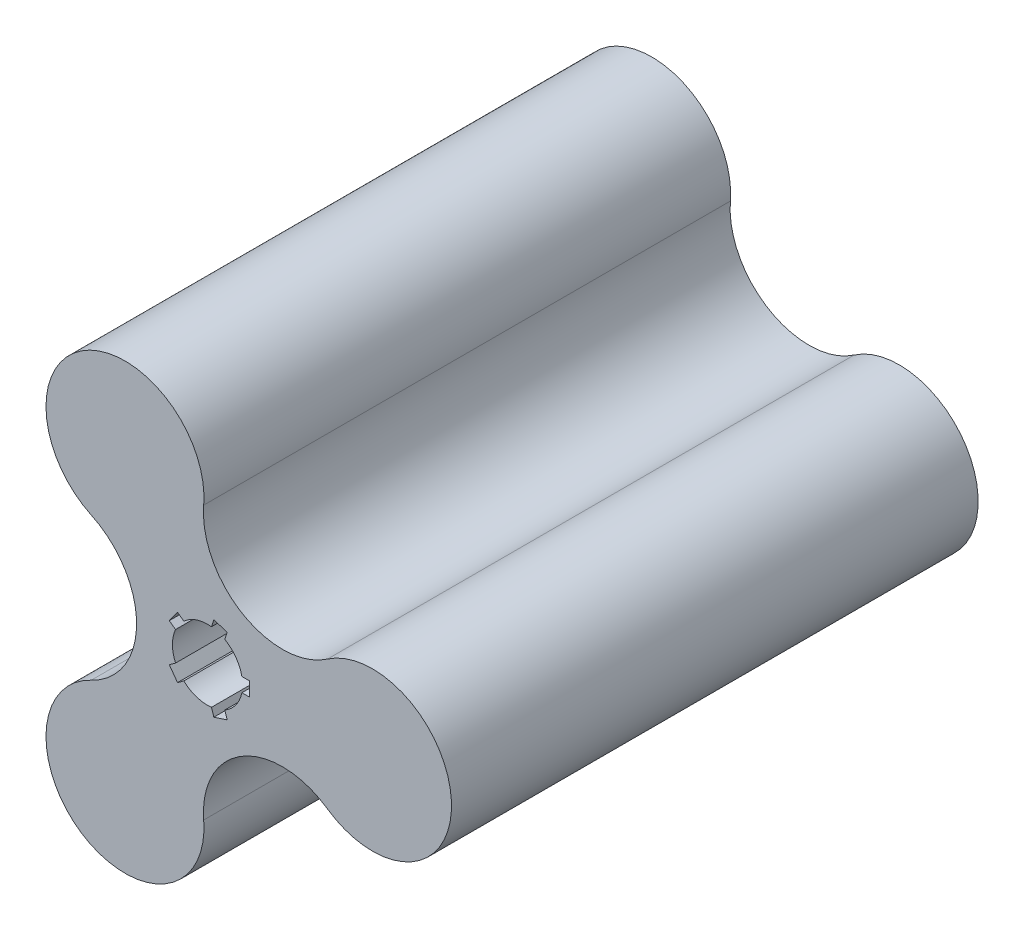
SolidWorks part; units mm, degrees
material "1023 Carbon Steel Sheet (SS)"
ref_plane "Front Plane" through (0, 0, 0) normal (0, 0, 1) x (1, 0, 0)
ref_plane "Top Plane" through (0, 0, 0) normal (0, 1, 0) x (1, 0, 0)
ref_plane "Right Plane" through (0, 0, 0) normal (1, 0, 0) x (0, 0, -1)
sketch "Sketch1" plane through (0, 0, 0) normal (0, 0, 1) x (1, 0, 0)
  arc A0 (34.1725, -18.4852) -> (34.1725, 18.4852) centre (47, 0) ccw
  arc A1 (-33.0949, -20.3516) -> (-1.0775, -38.8368) centre (-23.5, -40.7032) ccw
  arc A2 (-1.0775, 38.8368) -> (-33.0949, 20.3516) centre (-23.5, 40.7032) ccw
  arc A3 (-33.0949, -20.3516) -> (-33.0949, 20.3516) centre (-42.6898, 0) ccw
  arc A4 (-1.0775, 38.8368) -> (34.1725, 18.4852) centre (21.3449, 36.9705) ccw
  arc A5 (34.1725, -18.4852) -> (-1.0775, -38.8368) centre (21.3449, -36.9705) ccw
  point P14 (0, 0)
  point P17 (0, 0)
  dimension "D1" = 45
  dimension "D4" = 45
  dimension "D2" = 47
  dimension "D6" = 40.7032
  dimension "D7" = 47
  dimension "D3" = 3
  dimension "D5" = 3
extrude "Boss-Extrude1" add sketch "Sketch1" against normal blind 150
sketch "Sketch2" plane through (0, 0, 0) normal (0, 0, 1) x (1, 0, 0)
  line L5 (9.798, 2) -> (12, 2)
  line L7 (9.798, -2) -> (12, -2)
  line L8 (12, 2) -> (12, -2)
  line L11 (4.9298, -8.7004) -> (5.6103, -10.7946)
  line L12 (5.6103, -10.7946) -> (1.8061, -12.0307)
  line L13 (1.1256, -9.9364) -> (1.8061, -12.0307)
  line L15 (-6.7511, -7.3771) -> (-8.5326, -8.6715)
  line L16 (-8.5326, -8.6715) -> (-10.8838, -5.4354)
  line L17 (-9.1023, -4.1411) -> (-10.8838, -5.4354)
  line L19 (-9.1023, 4.1411) -> (-10.8838, 5.4354)
  line L20 (-10.8838, 5.4354) -> (-8.5326, 8.6715)
  line L21 (-6.7511, 7.3771) -> (-8.5326, 8.6715)
  line L23 (1.1256, 9.9364) -> (1.8061, 12.0307)
  line L24 (1.8061, 12.0307) -> (5.6103, 10.7946)
  line L25 (4.9298, 8.7004) -> (5.6103, 10.7946)
  arc A0 (-9.1023, 4.1411) -> (-9.1023, -4.1411) centre (0, 0) ccw
  arc A1 (-6.7511, -7.3771) -> (1.1256, -9.9364) centre (0, 0) ccw
  arc A2 (4.9298, -8.7004) -> (9.798, -2) centre (0, 0) ccw
  arc A3 (9.798, 2) -> (4.9298, 8.7004) centre (0, 0) ccw
  arc A4 (1.1256, 9.9364) -> (-6.7511, 7.3771) centre (0, 0) ccw
  point P3 (0, 10)
  point P4 (0, 0)
  point P6 (0, 0)
  point P25 (-0.4964, -0.1066)
  point P28 (0, 0)
  dimension "D1" = 20
  dimension "D2" = 4
  dimension "D3" = 12
  dimension "D4" = 5
  dimension "D5" = 12
  dimension "D6" = 12
  dimension "D7" = 2.202
extrude "Cut-Extrude1" cut sketch "Sketch2" against normal through all
